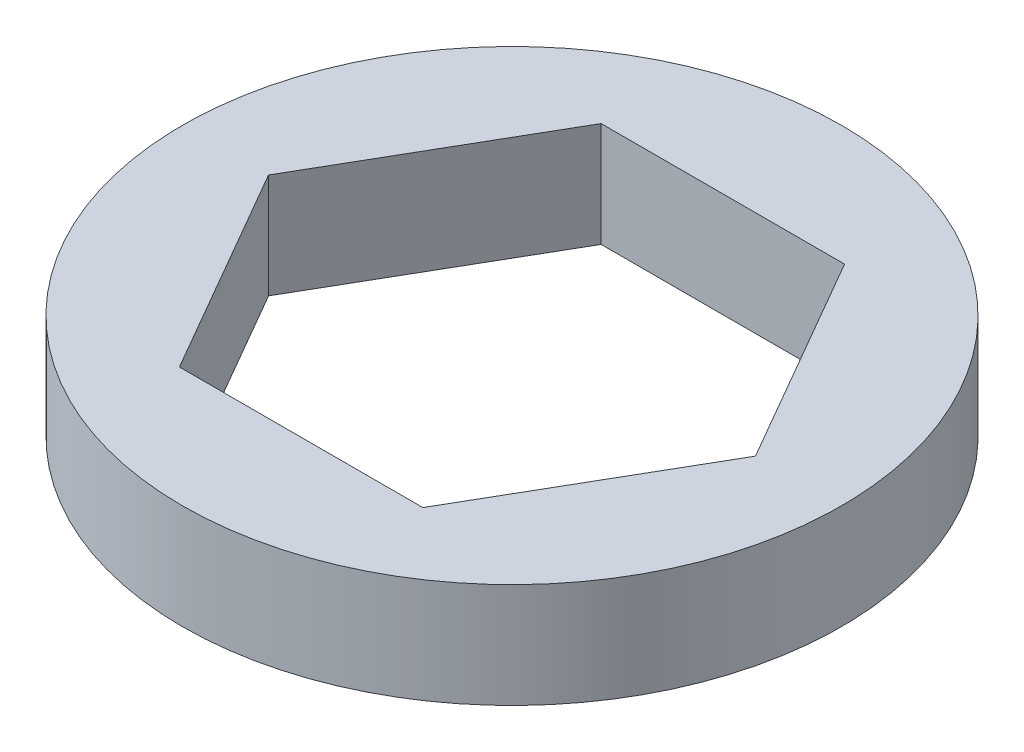
SolidWorks part; units mm, degrees
ref_plane "Front Plane" through (0, 0, 0) normal (0, 0, 1) x (1, 0, 0)
ref_plane "Top Plane" through (0, 0, 0) normal (0, 1, 0) x (1, 0, 0)
ref_plane "Right Plane" through (0, 0, 0) normal (1, 0, 0) x (0, 0, -1)
sketch "Sketch1" plane through (0, 0, 0) normal (0, 1, 0) x (1, 0, 0)
  line L1 (7.3837, 0) -> (3.6918, 6.3944)
  line L2 (3.6918, 6.3944) -> (-3.6918, 6.3944)
  line L3 (-3.6918, 6.3944) -> (-7.3837, 0)
  line L4 (-7.3837, 0) -> (-3.6918, -6.3945)
  line L5 (-3.6918, -6.3945) -> (3.6918, -6.3944)
  line L6 (3.6918, -6.3944) -> (7.3837, 0)
  circle A0 centre (0, 0) radius 6.3944 construction
  circle A1 centre (0, 0) radius 9.9949
  dimension "D1" = 12.7889
  dimension "D2" = 19.9898
extrude "Boss-Extrude1" add sketch "Sketch1" along normal blind 3.175
